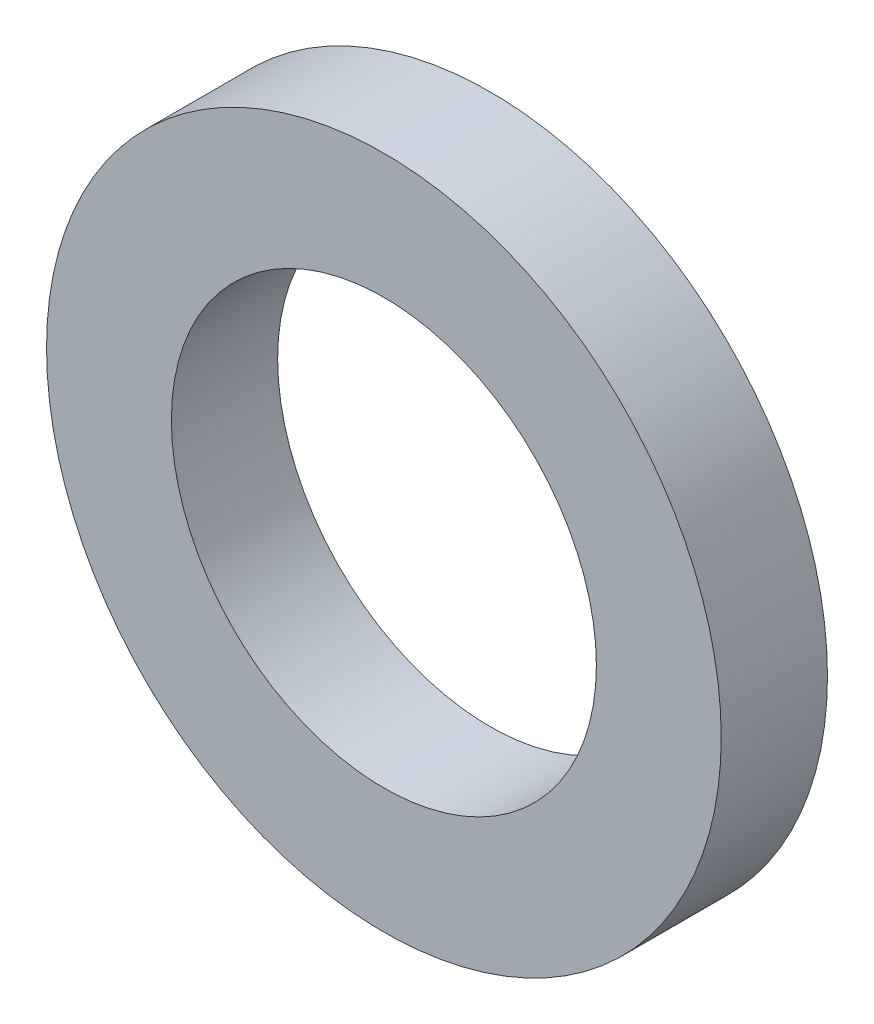
SolidWorks part; units mm, degrees
ref_plane "Front Plane" through (0, 0, 0) normal (1, 0, 0) x (0, 1, 0)
ref_plane "Top Plane" through (0, 0, 0) normal (0, 0, 1) x (0, 1, 0)
ref_plane "Right Plane" through (0, 0, 0) normal (0, 1, 0) x (-1, 0, 0)
sketch "Sketch1" plane through (0, 0, 0) normal (0, 0, 1) x (0, 1, 0)
  circle A0 centre (0, 0) radius 4
  circle A1 centre (0, 0) radius 6.35
  dimension "D1" = 8
  dimension "D2" = 12.7
extrude "Boss-Extrude1" add sketch "Sketch1" along normal blind 2
